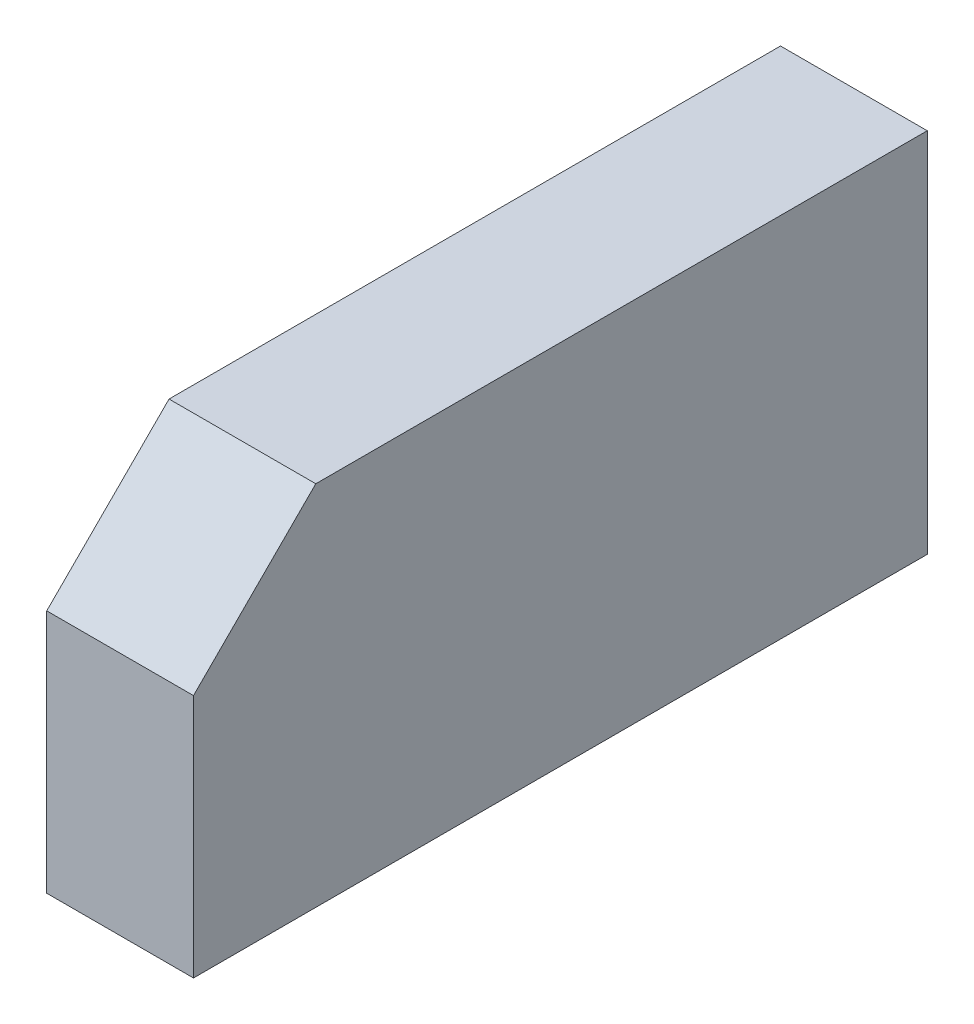
SolidWorks part; units mm, degrees
material "ABS"
ref_plane "Спереди" through (0, 0, 0) normal (0, 0, 1) x (1, 0, 0)
ref_plane "Сверху" through (0, 0, 0) normal (0, 1, 0) x (1, 0, 0)
ref_plane "Справа" through (0, 0, 0) normal (1, 0, 0) x (0, 0, -1)
other "Configuration Table"
sketch "Эскиз1" plane through (0, 0, 0) normal (0, 1, 0) x (1, 0, 0)
  line L1 (0, 30) -> (6, 30)
  line L2 (0, 30) -> (0, 0)
  line L3 (0, 0) -> (6, 0)
  line L4 (6, 30) -> (6, 0)
  dimension "D1" = 30
  dimension "D2" = 6
extrude "Бобышка-Вытянуть1" add sketch "Эскиз1" along normal blind 15
chamfer "Фаска1" distance 5 angle 45 1 edges at (3, 15, 0)
